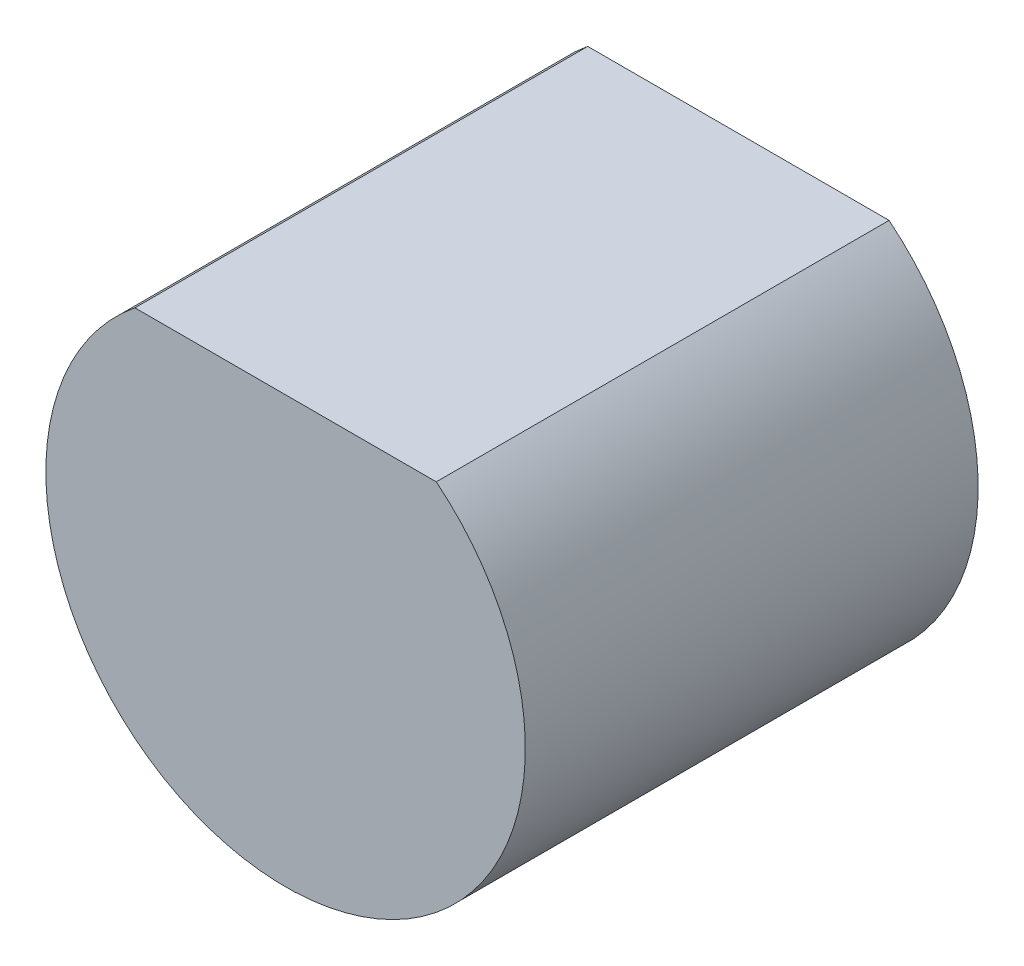
SolidWorks part; units mm, degrees
ref_plane "Front Plane" through (0, 0, 0) normal (0, 0, 1) x (1, 0, 0)
ref_plane "Top Plane" through (0, 0, 0) normal (0, 1, 0) x (1, 0, 0)
ref_plane "Right Plane" through (0, 0, 0) normal (1, 0, 0) x (0, 0, -1)
sketch "Sketch1" plane through (0, 0, 0) normal (0, 0, 1) x (1, 0, 0)
  circle A0 centre (0, 0) radius 2.286
  dimension "D1" = 4.572
extrude "Boss-Extrude1" add sketch "Sketch1" along normal blind 4.318
sketch "Sketch2" plane through (0, 0, 4.318) normal (0, 0, 1) x (1, 0, 0)
  line L0 (-1.4368, 1.778) -> (1.4368, 1.778)
  circle A0 centre (0, 0) radius 2.286 construction
  arc A1 (-1.4368, 1.778) -> (1.4368, 1.778) centre (0, 0) cw
  dimension "D1" = 1.778
extrude "Cut-Extrude1" cut sketch "Sketch2" against normal blind 4.318
